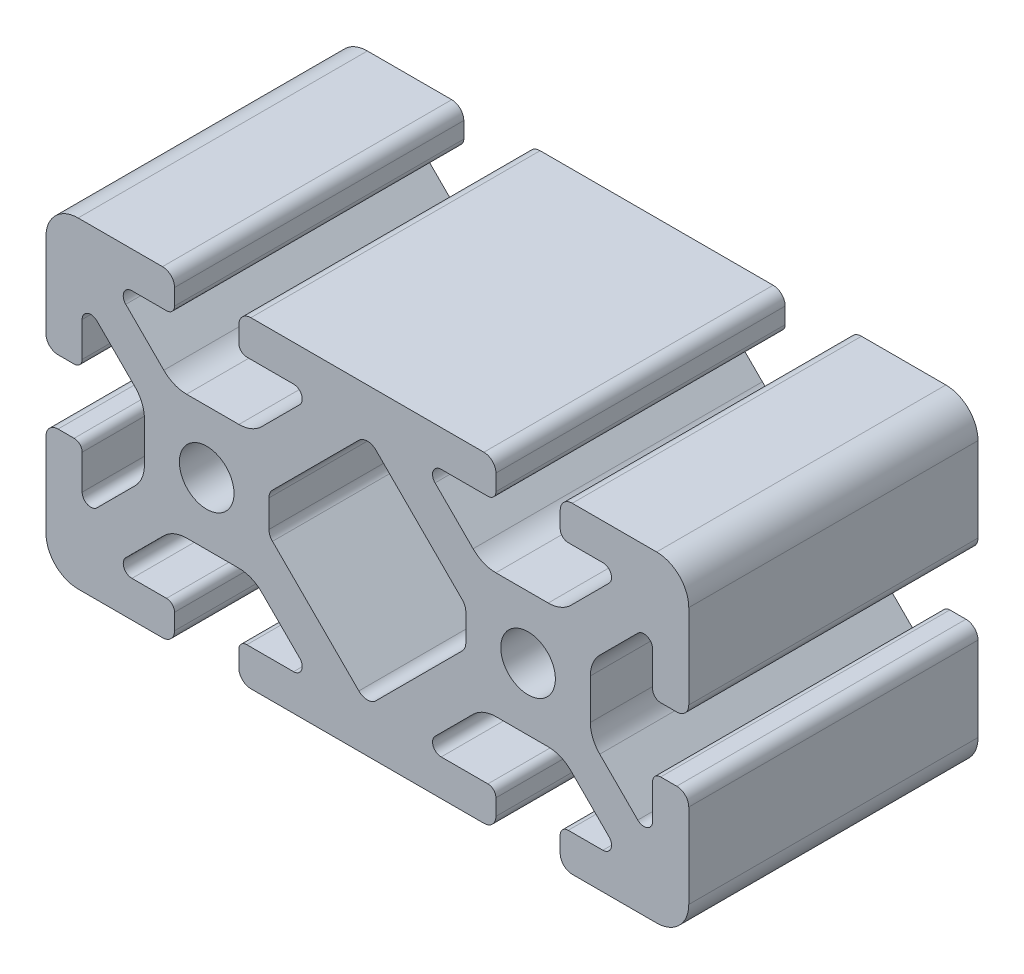
SolidWorks part; units mm, degrees
ref_plane "Front Plane" through (0, 0, 0) normal (0, 0, 1) x (1, 0, 0)
ref_plane "Top Plane" through (0, 0, 0) normal (0, 1, 0) x (1, 0, 0)
ref_plane "Right Plane" through (0, 0, 0) normal (1, 0, 0) x (0, 0, -1)
sketch "Sketch1" plane through (0, 0, 0) normal (0, 0, 1) x (1, 0, 0)
  line L0 (-27.75, -7.75) -> (-12.25, 7.75) construction
  line L1 (-36, -20) -> (-25.5, -20)
  line L2 (-40, -16) -> (-40, -5.5)
  line L3 (-36, 20) -> (-25.5, 20)
  line L4 (40, -16) -> (40, -5.5)
  line L5 (-40, -20) -> (40, 20) construction
  line L6 (-40, 20) -> (40, -20) construction
  line L7 (-24, 18.5) -> (-24, 16.5)
  line L8 (-29.3076, -15.5) -> (-25, -15.5)
  line L9 (35.5, 9.3076) -> (35.5, 5)
  line L10 (-29.3076, 15.5) -> (-25, 15.5)
  line L11 (24, 18.5) -> (24, 16.5)
  line L12 (-24, -16.5) -> (-24, -18.5)
  line L13 (-38.5, -4) -> (-36.5, -4)
  line L14 (24, -16.5) -> (24, -18.5)
  line L15 (-38.5, 4) -> (-36.5, 4)
  line L16 (36.5, 4) -> (38.5, 4)
  line L17 (36.5, -4) -> (38.5, -4)
  line L18 (-16, 18.5) -> (-16, 16.5)
  line L19 (16, 18.5) -> (16, 16.5)
  line L20 (-16, -16.5) -> (-16, -18.5)
  line L21 (16, -16.5) -> (16, -18.5)
  line L22 (-11.8107, 2.7607) -> (-1.0607, 13.5107)
  line L23 (-11.8107, -2.7607) -> (-1.0607, -13.5107)
  line L24 (1.0607, 13.5107) -> (11.8107, 2.7607)
  line L25 (1.0607, -13.5107) -> (11.8107, -2.7607)
  line L26 (-12.25, 1.7) -> (-12.25, -1.7)
  line L27 (12.25, 1.7) -> (12.25, -1.7)
  line L28 (-12.25, 0) -> (12.25, 0) construction
  line L29 (-40, 5.5) -> (-40, 16)
  line L30 (-35.5, -5) -> (-35.5, -9.3076)
  line L31 (-14.5, 20) -> (14.5, 20)
  line L32 (-15, 15.5) -> (-9.1881, 15.5)
  line L33 (25.5, 20) -> (36, 20)
  line L34 (25, 15.5) -> (29.3076, 15.5)
  line L35 (25, -15.5) -> (29.3076, -15.5)
  line L36 (25.5, -20) -> (36, -20)
  line L37 (-15, -15.5) -> (-9.1881, -15.5)
  line L38 (-14.5, -20) -> (14.5, -20)
  line L39 (35.5, -5) -> (35.5, -9.3076)
  line L40 (40, 5.5) -> (40, 16)
  line L41 (-35.5, 9.3076) -> (-35.5, 5)
  line L42 (-22.5081, 7.75) -> (-15.9876, 7.75)
  line L43 (-27.75, 2.5081) -> (-27.75, -2.5081)
  line L44 (-22.5081, -7.75) -> (-15.9876, -7.75)
  line L46 (8.4245, 13.6563) -> (13.1592, 8.9216)
  line L47 (15.9876, -7.75) -> (22.5081, -7.75)
  line L49 (15.9876, 7.75) -> (22.5081, 7.75)
  line L50 (27.75, -2.5081) -> (27.75, 2.5081)
  line L51 (12.25, -7.75) -> (27.75, 7.75) construction
  line L52 (12.25, 7.75) -> (27.75, -7.75) construction
  line L53 (13.1592, -8.9216) -> (8.4245, -13.6563)
  line L54 (-13.1592, 8.9216) -> (-8.4245, 13.6563)
  line L55 (-13.1592, -8.9216) -> (-8.4245, -13.6563)
  line L56 (25.3365, 8.9216) -> (30.0713, 13.6563)
  line L57 (28.9216, 5.3365) -> (33.6563, 10.0713)
  line L58 (25.3365, -8.9216) -> (30.0713, -13.6563)
  line L59 (28.9216, -5.3365) -> (33.6563, -10.0713)
  line L60 (-33.6563, 10.0713) -> (-28.9216, 5.3365)
  line L61 (-30.0713, 13.6563) -> (-25.3365, 8.9216)
  line L62 (-33.6563, -10.0713) -> (-28.9216, -5.3365)
  line L63 (-30.0713, -13.6563) -> (-25.3365, -8.9216)
  line L64 (-27.75, 7.75) -> (-12.25, -7.75) construction
  line L65 (12.25, -1.7) -> (12.25, 1.7)
  line L66 (-12.25, 1.7) -> (-12.25, -1.7)
  line L67 (9.1881, -15.5) -> (15, -15.5)
  line L68 (9.1881, 15.5) -> (15, 15.5)
  arc A0 (12.25, -1.7) -> (11.8107, -2.7607) centre (10.75, -1.7) cw
  arc A1 (12.25, 1.7) -> (11.8107, 2.7607) centre (10.75, 1.7) ccw
  arc A2 (-12.25, 1.7) -> (-11.8107, 2.7607) centre (-10.75, 1.7) cw
  arc A3 (-12.25, -1.7) -> (-11.8107, -2.7607) centre (-10.75, -1.7) ccw
  arc A4 (1.0607, -13.5107) -> (-1.0607, -13.5107) centre (0, -12.45) cw
  arc A5 (1.0607, 13.5107) -> (-1.0607, 13.5107) centre (0, 12.45) ccw
  circle A6 centre (-20, 0) radius 3.4
  circle A7 centre (20, 0) radius 3.4
  arc A8 (-40, 16) -> (-36, 20) centre (-36, 16) cw
  arc A9 (36, 20) -> (40, 16) centre (36, 16) cw
  arc A10 (36, -20) -> (40, -16) centre (36, -16) ccw
  arc A11 (-36, -20) -> (-40, -16) centre (-36, -16) cw
  arc A12 (-24, 18.5) -> (-25.5, 20) centre (-25.5, 18.5) ccw
  arc A13 (-38.5, 4) -> (-40, 5.5) centre (-38.5, 5.5) cw
  arc A14 (-38.5, -4) -> (-40, -5.5) centre (-38.5, -5.5) ccw
  arc A15 (-24, -18.5) -> (-25.5, -20) centre (-25.5, -18.5) cw
  arc A16 (-16, -18.5) -> (-14.5, -20) centre (-14.5, -18.5) ccw
  arc A17 (16, -18.5) -> (14.5, -20) centre (14.5, -18.5) cw
  arc A18 (24, -18.5) -> (25.5, -20) centre (25.5, -18.5) ccw
  arc A19 (38.5, -4) -> (40, -5.5) centre (38.5, -5.5) cw
  arc A20 (38.5, 4) -> (40, 5.5) centre (38.5, 5.5) ccw
  arc A21 (24, 18.5) -> (25.5, 20) centre (25.5, 18.5) cw
  arc A22 (16, 18.5) -> (14.5, 20) centre (14.5, 18.5) ccw
  arc A23 (-16, 18.5) -> (-14.5, 20) centre (-14.5, 18.5) cw
  arc A24 (-24, 16.5) -> (-25, 15.5) centre (-25, 16.5) cw
  arc A25 (-16, 16.5) -> (-15, 15.5) centre (-15, 16.5) ccw
  arc A26 (16, 16.5) -> (15, 15.5) centre (15, 16.5) cw
  arc A27 (24, 16.5) -> (25, 15.5) centre (25, 16.5) ccw
  arc A28 (36.5, 4) -> (35.5, 5) centre (36.5, 5) cw
  arc A29 (36.5, -4) -> (35.5, -5) centre (36.5, -5) ccw
  arc A30 (24, -16.5) -> (25, -15.5) centre (25, -16.5) cw
  arc A31 (16, -16.5) -> (15, -15.5) centre (15, -16.5) ccw
  arc A32 (-16, -16.5) -> (-15, -15.5) centre (-15, -16.5) cw
  arc A33 (-24, -16.5) -> (-25, -15.5) centre (-25, -16.5) ccw
  arc A34 (-36.5, -4) -> (-35.5, -5) centre (-36.5, -5) cw
  arc A35 (-36.5, 4) -> (-35.5, 5) centre (-36.5, 5) ccw
  arc A36 (25.3365, -8.9216) -> (22.5081, -7.75) centre (22.5081, -11.75) ccw
  arc A37 (25.3365, 8.9216) -> (22.5081, 7.75) centre (22.5081, 11.75) cw
  arc A38 (13.1592, 8.9216) -> (15.9876, 7.75) centre (15.9876, 11.75) ccw
  arc A39 (13.1592, -8.9216) -> (15.9876, -7.75) centre (15.9876, -11.75) cw
  arc A40 (-13.1592, -8.9216) -> (-15.9876, -7.75) centre (-15.9876, -11.75) ccw
  arc A41 (-25.3365, -8.9216) -> (-22.5081, -7.75) centre (-22.5081, -11.75) cw
  arc A42 (-28.9216, -5.3365) -> (-27.75, -2.5081) centre (-31.75, -2.5081) ccw
  arc A43 (-13.1592, 8.9216) -> (-15.9876, 7.75) centre (-15.9876, 11.75) cw
  arc A44 (-25.3365, 8.9216) -> (-22.5081, 7.75) centre (-22.5081, 11.75) ccw
  arc A45 (-28.9216, 5.3365) -> (-27.75, 2.5081) centre (-31.75, 2.5081) cw
  arc A46 (-8.4245, 13.6563) -> (-9.1881, 15.5) centre (-9.1881, 14.42) ccw
  arc A47 (8.4245, 13.6563) -> (9.1881, 15.5) centre (9.1881, 14.42) cw
  arc A48 (30.0713, 13.6563) -> (29.3076, 15.5) centre (29.3076, 14.42) ccw
  arc A49 (33.6563, 10.0713) -> (35.5, 9.3076) centre (34.42, 9.3076) cw
  arc A50 (33.6563, -10.0713) -> (35.5, -9.3076) centre (34.42, -9.3076) ccw
  arc A51 (30.0713, -13.6563) -> (29.3076, -15.5) centre (29.3076, -14.42) cw
  arc A52 (8.4245, -13.6563) -> (9.1881, -15.5) centre (9.1881, -14.42) ccw
  arc A53 (-8.4245, -13.6563) -> (-9.1881, -15.5) centre (-9.1881, -14.42) cw
  arc A54 (-30.0713, -13.6563) -> (-29.3076, -15.5) centre (-29.3076, -14.42) ccw
  arc A55 (-33.6563, -10.0713) -> (-35.5, -9.3076) centre (-34.42, -9.3076) cw
  arc A56 (-30.0713, 13.6563) -> (-29.3076, 15.5) centre (-29.3076, 14.42) cw
  arc A57 (-33.6563, 10.0713) -> (-35.5, 9.3076) centre (-34.42, 9.3076) ccw
  arc A58 (28.9216, -5.3365) -> (27.75, -2.5081) centre (31.75, -2.5081) cw
  arc A59 (28.9216, 5.3365) -> (27.75, 2.5081) centre (31.75, 2.5081) ccw
  point P0 (0, 0)
  point P56 (0, -14.5713)
  point P59 (0, 14.5713)
  point P84 (-40, 4)
  point P91 (-16, -20)
  point P96 (24, -20)
  point P101 (40, 4)
  point P104 (24, 20)
  point P107 (16, 20)
  point P110 (-16, 20)
  point P115 (-16, 15.5)
  point P118 (16, 15.5)
  point P121 (24, 15.5)
  point P126 (35.5, -4)
  point P129 (24, -15.5)
  point P134 (-16, -15.5)
  point P139 (-35.5, -4)
  point P142 (-35.5, 4)
  point P187 (6.5808, 15.5)
  point P198 (6.5808, -15.5)
  dimension "D13" = 1.5
  dimension "D15" = 24.9
  dimension "D16" = 7.75
  dimension "D17" = 6.8
  dimension "D18" = 7.75
  dimension "D19" = 4
  dimension "D24" = 1.5
  dimension "D25" = 1
  dimension "D38" = 4
  dimension "D39" = 1.08
  dimension "D40" = 4
  dimension "D1" = 80
  dimension "D2" = 40
  dimension "D3" = 4.5
  dimension "D4" = 4.5
  dimension "D5" = 4.5
  dimension "D6" = 4.5
  dimension "D7" = 16
  dimension "D8" = 16
  dimension "D9" = 16
  dimension "D10" = 16
  dimension "D11" = 32
  dimension "D12" = 8
  dimension "D14" = 24.5
  dimension "D20" = 15.5
  dimension "D21" = 15.5
  dimension "D22" = 15.5
  dimension "D23" = 15.5
  dimension "D26" = 5.31
  dimension "D27" = 5.31
  dimension "D28" = 5.31
  dimension "D29" = 5.31
  dimension "D30" = 5.07
  dimension "D31" = 2.535
  dimension "D32" = 5.07
  dimension "D33" = 2.535
  dimension "D34" = 5.07
  dimension "D35" = 2.535
  dimension "D36" = 5.07
  dimension "D37" = 2.535
extrude "Boss-Extrude1" add sketch "Sketch1" along normal blind 36 contours A59 L57 A49 L9 A28 L16 A20 L40 A9 L33 A21 L11 A27 L34 A48 L56 A37 L49 A38 L46 A47 L68 A26 L19 A22 L31 A23 L18 A25 L32 A46 L54 A43 L42 A44 L61 A56 L10 A24 L7 A12 L3 A8 L29 A13 L15 A35 L41 A57 L60 A45
